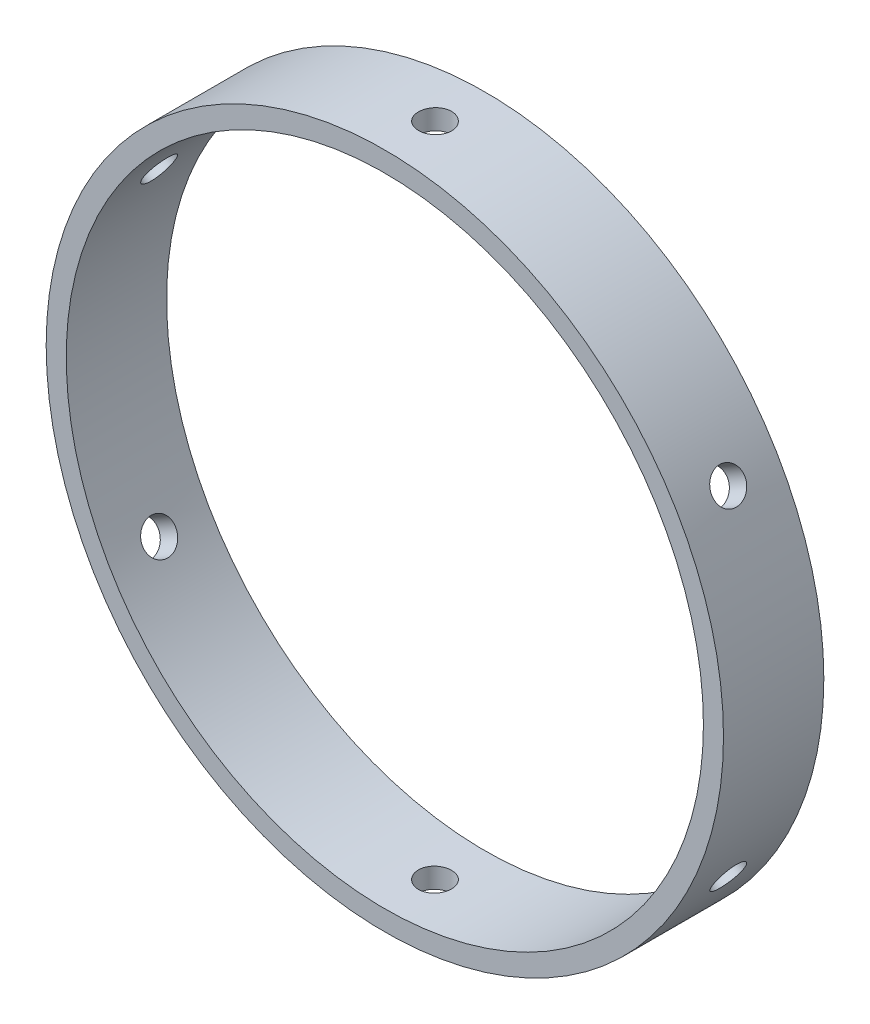
SolidWorks part; units mm, degrees
ref_plane "Front Plane" through (0, 0, 0) normal (0, 0, 1) x (1, 0, 0)
ref_plane "Top Plane" through (0, 0, 0) normal (0, 1, 0) x (1, 0, 0)
ref_plane "Right Plane" through (0, 0, 0) normal (1, 0, 0) x (0, 0, -1)
sketch "Sketch1" plane through (0, 0, 0) normal (0, 0, 1) x (1, 0, 0)
  line L0 (0, 31.75) -> (0, 33.75) construction
  circle A0 centre (0, 0) radius 31.75
  circle A1 centre (0, 0) radius 33.75
  dimension "D1" = 63.5
  dimension "D2" = 2
extrude "Boss-Extrude1" add sketch "Sketch1" along normal mid plane 10
sketch "Sketch2" plane through (0, 0, 0) normal (0, 1, 0) x (1, 0, 0)
  point P0 (0, 0)
hole_wizard "M4x0.7 Tapped Hole1" positions "Sketch2" profile "Sketch3" tap size "M4x0.7" standard "ANSI Metric"
sketch "Sketch3" plane through (0, 0, 0) normal (1, 0, 0) x (0, 0, -1)
  line L0 (0, 0) -> (0, 33.75)
  line L1 (0, 33.75) -> (1.65, 33.75)
  line L2 (1.65, 33.75) -> (1.65, 0)
  line L5 (1.65, 0) -> (0, 0)
  line L11 (0, -6.35) -> (0, 107.95) construction
  dimension "Thru Tap Drill Dia." = 3.3
  dimension "Thru Tap Drill Depth" = 33.75
cosmetic thread "Hole Thread1" parameters "D2"=4
pattern_circular "CirPattern1" count 6 over 360 about axis through (0, 0, 5) along (0, 0, -1) of "M4x0.7 Tapped Hole1"
cosmetic thread "Hole Thread2" parameters "D2"=4
cosmetic thread "Hole Thread3" parameters "D2"=4
cosmetic thread "Hole Thread4" parameters "D2"=4
cosmetic thread "Hole Thread5" parameters "D2"=4
cosmetic thread "Hole Thread6" parameters "D2"=4
